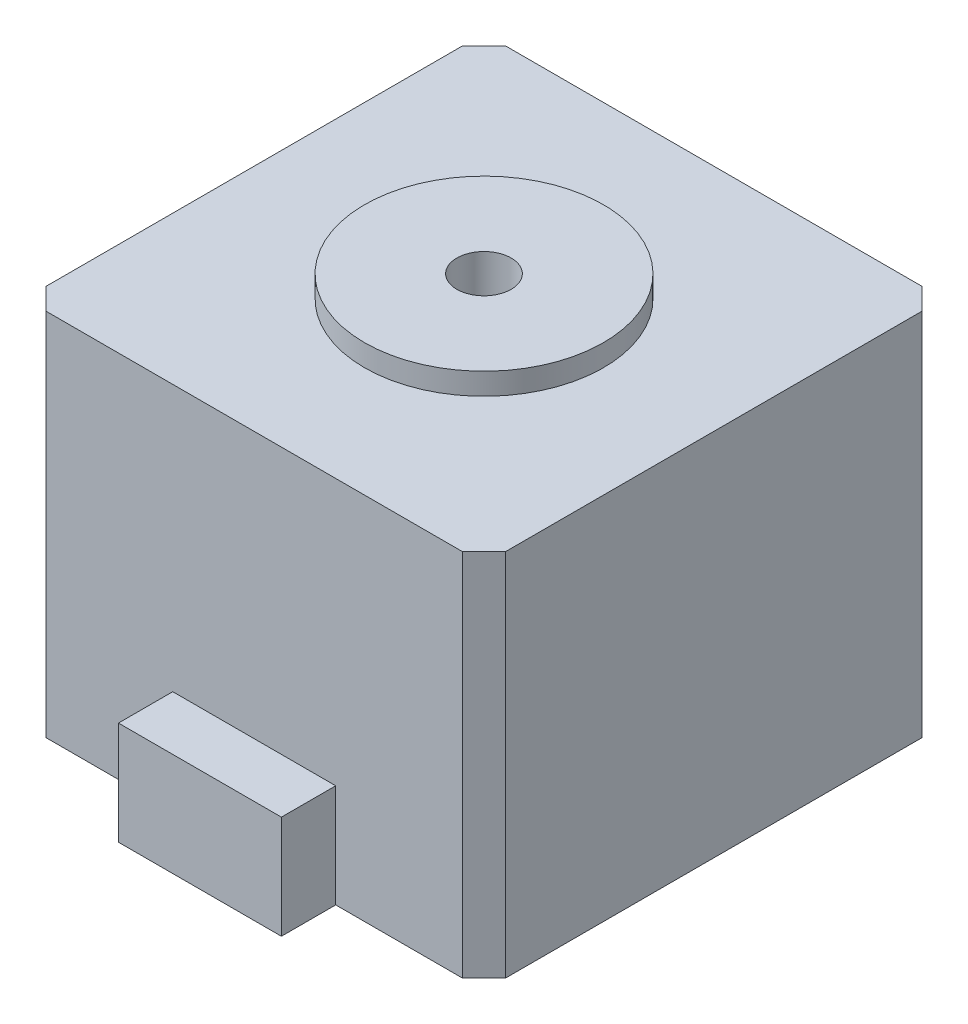
SolidWorks part; units mm, degrees
ref_plane "Front Plane" through (0, 0, 0) normal (0, 0, 1) x (1, 0, 0)
ref_plane "Top Plane" through (0, 0, 0) normal (0, 1, 0) x (1, 0, 0)
ref_plane "Right Plane" through (0, 0, 0) normal (1, 0, 0) x (0, 0, -1)
sketch "Sketch1" plane through (0, 0, 0) normal (0, 1, 0) x (1, 0, 0)
  line L1 (0, 0) -> (42.3, 0)
  line L2 (0, 0) -> (0, 42.3)
  line L3 (0, 42.3) -> (42.3, 42.3)
  line L4 (42.3, 0) -> (42.3, 42.3)
  dimension "D1" = 42.3
  dimension "D2" = 42.3
extrude "Boss-Extrude1" add sketch "Sketch1" along normal blind 34
chamfer "Chamfer2" distance 2 angle 45 4 edges at (42.3, 17, -42.3) (0, 17, -42.3) (0, 17, 0) (42.3, 17, 0)
sketch "Sketch2" plane through (0, 34, 0) normal (0, 1, 0) x (1, 0, 0)
  line L0 (21.15, 38.0694) -> (21.15, -5.6443) construction
  line L1 (0, 40.3) -> (0, 2) construction
  line L2 (42.3, 2) -> (42.3, 40.3) construction
  line L3 (38.6993, 21.15) -> (67.8251, 21.15) construction
  line L4 (40.3, 42.3) -> (2, 42.3) construction
  line L5 (2, 0) -> (40.3, 0) construction
  circle A0 centre (21.15, 21.15) radius 11
  dimension "D1" = 22
extrude "Boss-Extrude2" add sketch "Sketch2" along normal blind 2
sketch "Sketch3" plane through (0, 36, 0) normal (0, 1, 0) x (1, 0, 0)
  line L0 (21.15, 36.633) -> (21.15, 13.792) construction
  line L1 (0, 40.3) -> (0, 2) construction
  line L2 (42.3, 2) -> (42.3, 40.3) construction
  line L3 (2.8497, 21.15) -> (14.3227, 21.15) construction
  line L4 (40.3, 42.3) -> (2, 42.3) construction
  line L5 (2, 0) -> (40.3, 0) construction
  circle A1 centre (21.15, 21.15) radius 2.5
  dimension "D1" = 5
extrude "Cut-Extrude2" cut sketch "Sketch3" against normal blind 20
sketch "Sketch5" plane through (0, 0, 0) normal (0, 0, 1) x (1, 0, 0)
  line L0 (2, 0) -> (40.3, 0) construction
  line L1 (13.65, 0) -> (28.65, 0)
  line L2 (13.65, 0) -> (13.65, 9.5)
  line L3 (13.65, 9.5) -> (28.65, 9.5)
  line L4 (28.65, 0) -> (28.65, 9.5)
  line L5 (21.15, 17.9991) -> (21.15, 41.4455) construction
  line L6 (2, 34) -> (2, 0) construction
  line L7 (40.3, 0) -> (40.3, 34) construction
  dimension "D1" = 9.5
  dimension "D2" = 15
extrude "Boss-Extrude4" add sketch "Sketch5" along normal blind 5
